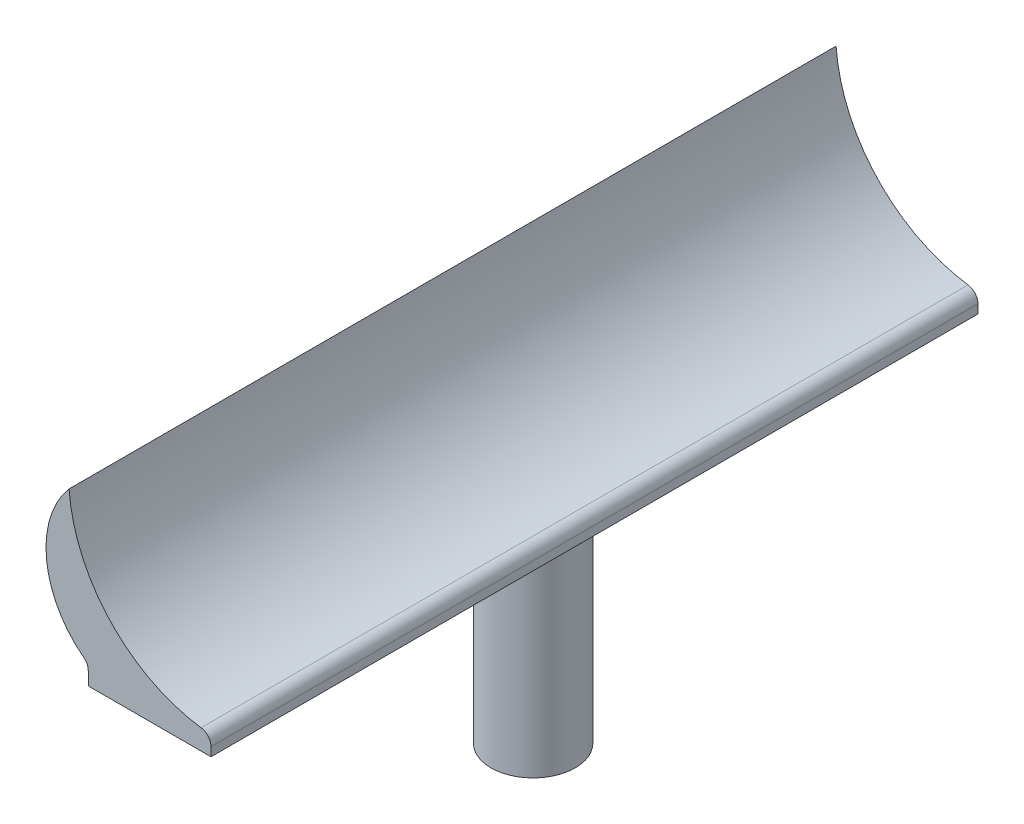
SolidWorks part; units mm, degrees
ref_plane "Front Plane" through (0, 0, 0) normal (0, 0, 1) x (1, 0, 0)
ref_plane "Top Plane" through (0, 0, 0) normal (0, 1, 0) x (1, 0, 0)
ref_plane "Right Plane" through (0, 0, 0) normal (1, 0, 0) x (0, 0, -1)
sketch "Sketch1" plane through (0, 0, 0) normal (0, 1, 0) x (1, 0, 0)
  circle A0 centre (0, 0) radius 11
  dimension "D1" = 22
extrude "Boss-Extrude1" add sketch "Sketch1" along normal blind 55
sketch "Sketch2" plane through (0, 0, 0) normal (0, 0, 1) x (1, 0, 0)
  line L0 (16, 55) -> (-16, 55)
  line L1 (-16, 55) -> (-16, 60)
  line L2 (16, 55) -> (16, 60)
  line L3 (0, 0) -> (0, 68.8766) construction
  line L4 (-11, 55) -> (-11, 0) construction
  line L5 (11, 55) -> (-11, 55) construction
  arc A0 (-16, 60) -> (-21, 97) centre (-2.0215, 80.7268) cw
  arc A2 (16, 60) -> (-21, 97) centre (18.8951, 99.8951) cw
  point P15 (0, 0)
  dimension "D4" = 25
  dimension "D7" = 40
  dimension "D1" = 10
  dimension "D2" = 32
  dimension "D3" = 42
  dimension "D5" = 5
  dimension "D6" = 5
extrude "Boss-Extrude2" add sketch "Sketch2" along normal mid plane 200
fillet "Fillet1" radius 3 2 edges at (-16, 60, 0) (16, 60, 0)
